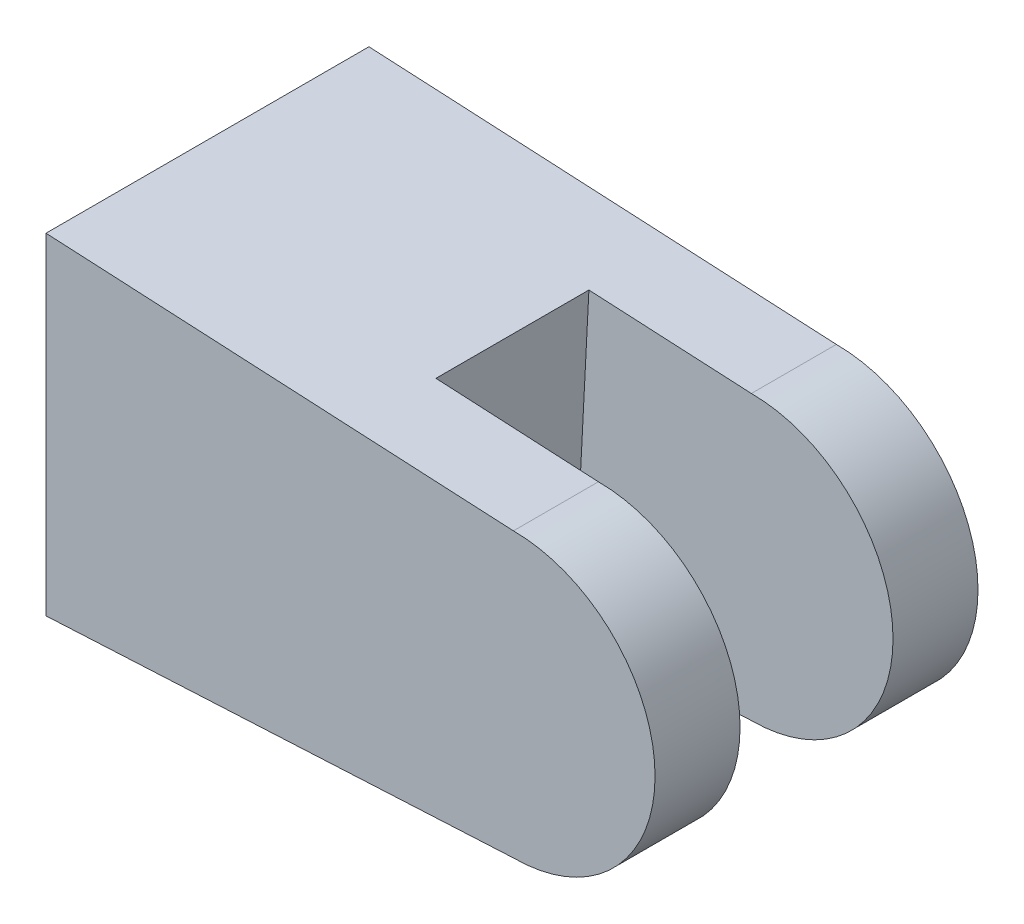
SolidWorks part; units mm, degrees
ref_plane "Front Plane" through (0, 0, 0) normal (0, 0, 1) x (1, 0, 0)
ref_plane "Top Plane" through (0, 0, 0) normal (0, 1, 0) x (1, 0, 0)
ref_plane "Right Plane" through (0, 0, 0) normal (1, 0, 0) x (0, 0, -1)
sketch "Sketch1" plane through (0, 0, 0) normal (0, 0, 1) x (1, 0, 0)
  line L0 (0, 0) -> (-165, 0) construction
  line L1 (-165, -58.5) -> (-165, 58.5)
  line L2 (-165, 58.5) -> (0, 50)
  line L3 (-165, -58.5) -> (0, -50)
  arc A0 (0, -50) -> (0, 50) centre (0, 0) ccw
  dimension "D1" = 100
  dimension "D2" = 165
  dimension "D3" = 58.5
extrude "Boss-Extrude1" add sketch "Sketch1" along normal mid plane 114
sketch "Sketch2" plane through (-165, 0, 0) normal (-1, 0, 0) x (0, 0, 1)
  circle A0 centre (0, 0) radius 37.5
  dimension "D1" = 75
extrude "Boss-Extrude2" add sketch "Sketch2" along normal blind 2
sketch "Sketch3" plane through (2.5689, 49.8677, 0) normal (0.0514, 0.9987, 0) x (0.9987, -0.0514, 0)
  line L0 (50, -57) -> (50, 57) construction
  line L1 (50, 27) -> (-60, 27)
  line L2 (50, 27) -> (50, -27)
  line L3 (50, -27) -> (-60, -27)
  line L4 (-60, 27) -> (-60, -27)
  point P6 (50, 0)
  dimension "D1" = 54
  dimension "D2" = 110
extrude "Cut-Extrude1" cut sketch "Sketch3" against normal through all both and the other way through all
